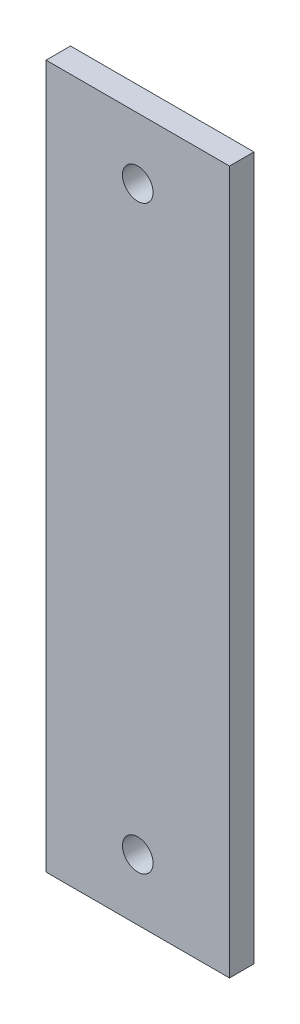
SolidWorks part; units mm, degrees
material "Balsa"
ref_plane "Plan de face" through (0, 0, 0) normal (0, 0, 1) x (1, 0, 0)
ref_plane "Plan de dessus" through (0, 0, 0) normal (0, 1, 0) x (1, 0, 0)
ref_plane "Plan de droite" through (0, 0, 0) normal (1, 0, 0) x (0, 0, -1)
sketch "Esquisse1" plane through (0, 0, 0) normal (0, 0, 1) x (1, 0, 0)
  line L0 (-5.9883, 0) -> (0, 0) construction
  line L5 (-15, 57.5) -> (15, 57.5)
  line L6 (-15, 57.5) -> (-15, -57.5)
  line L7 (-15, -57.5) -> (15, -57.5)
  line L8 (15, 57.5) -> (15, -57.5)
  line L9 (-15, 57.5) -> (15, -57.5) construction
  line L10 (-15, -57.5) -> (15, 57.5) construction
  circle A8 centre (0, 47.5) radius 2.5
  circle A9 centre (0, -47.5) radius 2.5
  point P0 (0, 0)
  dimension "D3" = 5
  dimension "D4" = 10
  dimension "D1" = 115
  dimension "D2" = 30
extrude "Boss.-Extru.1" add sketch "Esquisse1" along normal blind 4
